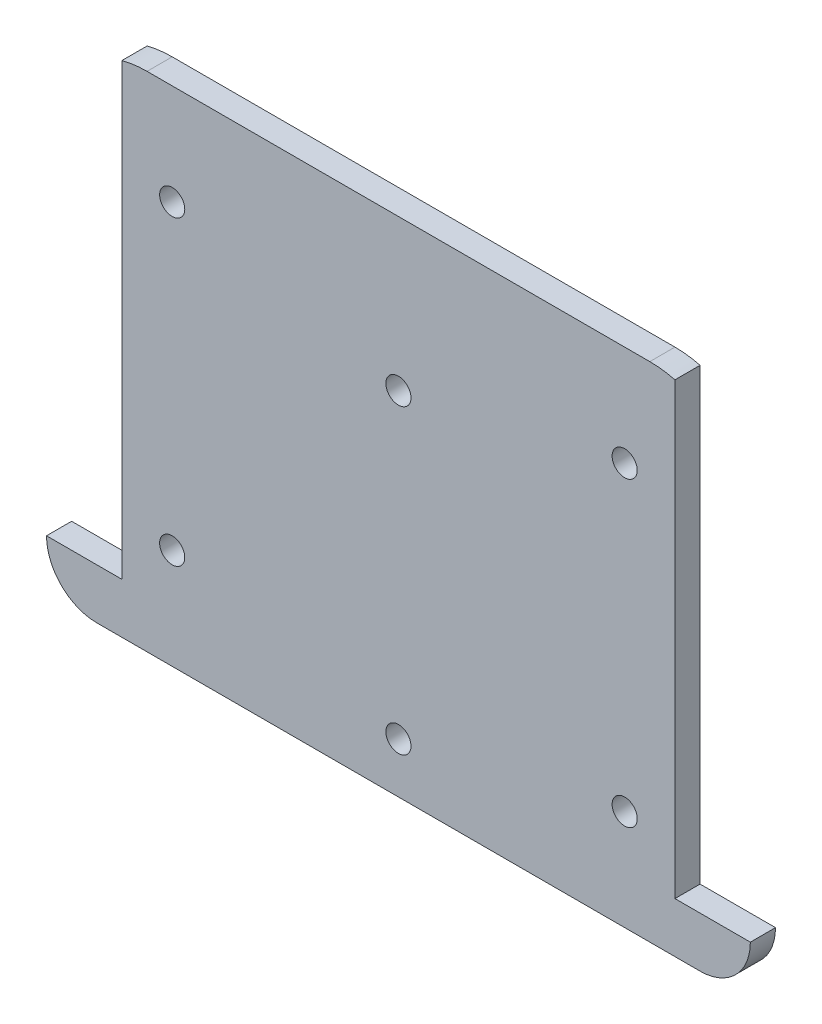
SolidWorks part; units mm, degrees
ref_plane "Front Plane" through (0, 0, 0) normal (0, 0, 1) x (1, 0, 0)
ref_plane "Top Plane" through (0, 0, 0) normal (0, 1, 0) x (1, 0, 0)
ref_plane "Right Plane" through (0, 0, 0) normal (1, 0, 0) x (0, 0, -1)
sketch "Sketch1" plane through (0, 0, 0) normal (0, 0, 1) x (1, 0, 0)
  line L5 (-60, -50) -> (60, -50)
  line L6 (-70, -40) -> (-70, 30)
  line L7 (-50, 50) -> (50, 50)
  line L8 (70, -40) -> (70, 30)
  line L9 (-70, -50) -> (70, 50) construction
  line L10 (-70, 50) -> (70, -50) construction
  arc A0 (60, -50) -> (70, -40) centre (60, -40) ccw
  arc A1 (-60, -50) -> (-70, -40) centre (-60, -40) cw
  arc A2 (-70, 30) -> (-50, 50) centre (-50, 30) cw
  arc A3 (50, 50) -> (70, 30) centre (50, 30) cw
  point P0 (0, 0)
  point P1 (0, 0)
  dimension "D3" = 10
  dimension "D4" = 10
  dimension "D5" = 20
  dimension "D1" = 100
  dimension "D2" = 140
extrude "Boss-Extrude1" add sketch "Sketch1" along normal blind 5
sketch "Sketch2" plane through (0, 0, 5) normal (0, 0, 1) x (1, 0, 0)
  line L0 (0, 0) -> (-42.2072, 0) construction
  line L1 (-60, -50) -> (60, -50) construction
  line L3 (50, 50) -> (-50, 50) construction
  line L4 (-70, 30) -> (-70, -40) construction
  line L5 (0, 0) -> (0, 30) construction
  circle A4 centre (0, -40) radius 2.5
  circle A5 centre (-45, 30) radius 2.5
  circle A6 centre (45, 30) radius 2.5
  circle A7 centre (-45, -30) radius 2.5
  circle A8 centre (45, -30) radius 2.5
  dimension "D1" = 20
  dimension "D2" = 25
  dimension "D4" = 5
  dimension "D5" = 5
  dimension "D3" = 10
extrude "Cut-Extrude1" cut sketch "Sketch2" against normal blind 5
sketch "Sketch3" plane through (0, 0, 5) normal (0, 0, 1) x (1, 0, 0)
  line L0 (70, -40) -> (55, -40)
  line L1 (55, -40) -> (55, 49.3649)
  line L2 (70, -40) -> (70, 49.3649)
  line L3 (70, 49.3649) -> (55, 49.3649)
  line L4 (0, 0) -> (0, 39.117) construction
  line L5 (-70, -40) -> (-70, 49.3649)
  line L6 (-70, -40) -> (-55, -40)
  line L7 (-55, -40) -> (-55, 49.3649)
  line L8 (-70, 49.3649) -> (-55, 49.3649)
  arc A0 (70, 30) -> (50, 50) centre (50, 30) ccw construction
  dimension "D1" = 15
extrude "Cut-Extrude2" cut sketch "Sketch3" against normal blind 5
sketch "Sketch4" plane through (0, 0, 5) normal (0, 0, 1) x (1, 0, 0)
  circle A0 centre (0, 20) radius 2.5
  circle A1 centre (0, -40) radius 2.5 construction
  dimension "D2" = 5
  dimension "D1" = 60
extrude "Cut-Extrude3" cut sketch "Sketch4" against normal blind 5
